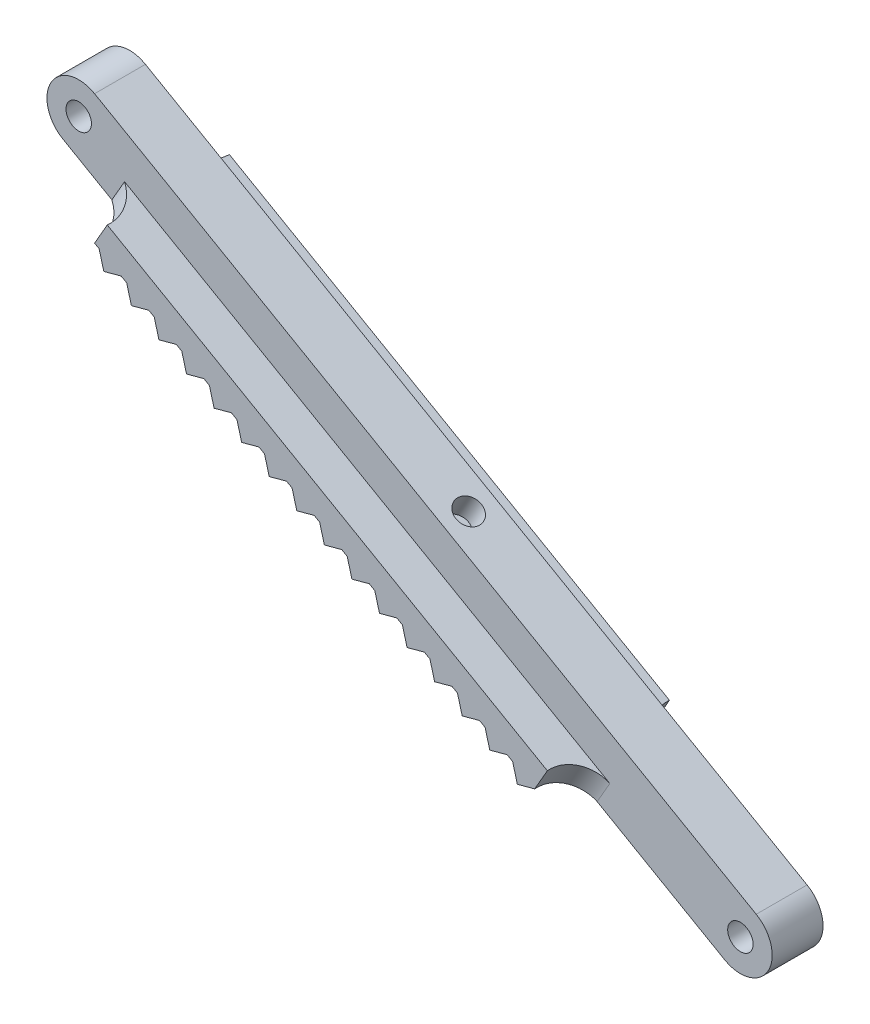
SolidWorks part; units mm, degrees
ref_plane "Спереди" through (0, 0, 0) normal (0, 0, 1) x (1, 0, 0)
ref_plane "Сверху" through (0, 0, 0) normal (0, 1, 0) x (1, 0, 0)
ref_plane "Справа" through (0, 0, 0) normal (1, 0, 0) x (0, 0, -1)
sketch "Sketch1" plane through (0, 0, 0) normal (0, 0, 1) x (1, 0, 0)
  line L0 (-5.265, 31.0446) -> (-57.3012, 60.9149) construction
  line L5 (-57.3012, 60.9149) -> (-5.265, 31.0446) construction
  line L6 (-56.0566, 63.083) -> (-4.0204, 33.2128)
  line L7 (-58.5458, 58.7467) -> (-6.5096, 28.8765)
  arc A2 (-56.0566, 63.083) -> (-58.5458, 58.7467) centre (-57.3012, 60.9149) ccw
  arc A3 (-6.5096, 28.8765) -> (-4.0204, 33.2128) centre (-5.265, 31.0446) ccw
  circle A4 centre (-57.3012, 60.9149) radius 1
  circle A5 centre (-5.265, 31.0446) radius 1
  point P2 (-31.2831, 45.9797)
  dimension "D3" = 2
  dimension "D1" = 60
  dimension "D2" = 5
extrude "Boss-Extrude1" add sketch "Sketch1" along normal blind 4
sketch "Sketch2" plane through (13.3435, 23.2454, 0) normal (0.4978, 0.8673, 0) x (0.8673, -0.4978, 0)
  line L0 (-50.3436, -2) -> (-46.6778, -2) construction
  line L2 (-48.4037, -4) -> (-48.4037, 0) construction
  circle A0 centre (-48.4037, -2) radius 1
  dimension "D1" = 2
extrude "Cut-Extrude1" cut sketch "Sketch2" against normal blind 2
sketch "Sketch3" plane through (0, 0, 0) normal (0, 0, -1) x (-1, 0, 0)
  line L0 (57.3012, 60.9149) -> (5.265, 31.0446) construction
sketch "Sketch4" plane through (10.8543, 18.9091, 0) normal (-0.4978, -0.8673, 0) x (0.8673, -0.4978, 0)
  line L0 (-77.201, 2) -> (-19.2917, 2) construction
  line L1 (-77.201, 4) -> (-77.201, 0) construction
  line L2 (-73.9186, 2) -> (-73.9186, 6.8) construction
  line L3 (-73.9186, 2) -> (-73.9186, -2.8) construction
  line L5 (-34.0104, 6.0447) -> (-34.0104, -2.4313) construction
  line L6 (-73.9186, 6.8) -> (-34.0104, 6.8)
  line L8 (-34.0104, -2.8) -> (-73.9186, -2.8)
  line L9 (-80.0213, 4) -> (-20.0213, 4) construction
  line L10 (-75.5799, 5.5) -> (-75.5799, 4) construction
  line L11 (-80.0213, 0) -> (-20.0213, 0) construction
  line L12 (-75.5799, 4) -> (-76.7485, 0)
  line L13 (-31.5748, 4) -> (-31.5748, 0)
  line L14 (-34.0104, -2.4313) -> (-34.0104, -2.8)
  arc A0 (-73.9186, 6.8) -> (-75.5799, 4) centre (-76.7401, 6.5812) cw
  arc A1 (-73.9186, -2.8) -> (-76.7485, 0) centre (-76.7188, -2.8) ccw
  arc A2 (-34.0104, 6.8) -> (-31.5748, 4) centre (-31.3926, 6.6178) ccw
  arc A3 (-31.5748, 0) -> (-34.0104, -2.8) centre (-31.3926, -2.6178) ccw
  dimension "D1" = 4.8
  dimension "D2" = 4.8
extrude "Boss-Extrude2" add sketch "Sketch4" against normal blind 2
sketch "Sketch5" plane through (0, 0, -2.8) normal (0, 0, -1) x (-1, 0, 0)
  line L0 (52.8991, 55.5053) -> (51.1646, 54.5096)
  line L1 (18.6419, 35.8407) -> (20.007, 35.4713)
  line L2 (20.007, 35.4713) -> (20.3765, 36.8364)
  line L3 (20.007, 35.4713) -> (19.5092, 36.3386) construction
  line L4 (20.8101, 37.0853) -> (22.1752, 36.7159)
  line L5 (22.1752, 36.7159) -> (22.5446, 38.081)
  line L6 (22.9783, 38.3299) -> (24.3434, 37.9605)
  line L7 (24.3434, 37.9605) -> (24.7128, 39.3256)
  line L8 (25.1464, 39.5745) -> (26.5115, 39.2051)
  line L9 (26.5115, 39.2051) -> (26.881, 40.5702)
  line L10 (27.3146, 40.8191) -> (28.6797, 40.4497)
  line L11 (28.6797, 40.4497) -> (29.0492, 41.8148)
  line L12 (29.4828, 42.0637) -> (30.8479, 41.6943)
  line L13 (30.8479, 41.6943) -> (31.2173, 43.0594)
  line L14 (31.651, 43.3083) -> (33.0161, 42.9389)
  line L15 (33.0161, 42.9389) -> (33.3855, 44.304)
  line L16 (33.8191, 44.5529) -> (35.1843, 44.1835)
  line L17 (35.1843, 44.1835) -> (35.5537, 45.5486)
  line L18 (35.9873, 45.7975) -> (37.3524, 45.4281)
  line L19 (37.3524, 45.4281) -> (37.7219, 46.7932)
  line L20 (38.1555, 47.0421) -> (39.5206, 46.6726)
  line L21 (39.5206, 46.6726) -> (39.89, 48.0378)
  line L22 (40.3237, 48.2867) -> (41.6888, 47.9172)
  line L23 (41.6888, 47.9172) -> (42.0582, 49.2823)
  line L24 (42.4919, 49.5313) -> (43.857, 49.1618)
  line L25 (43.857, 49.1618) -> (44.2264, 50.5269)
  line L26 (44.66, 50.7759) -> (46.0251, 50.4064)
  line L27 (46.0251, 50.4064) -> (46.3946, 51.7715)
  line L28 (46.8282, 52.0205) -> (48.1933, 51.651)
  line L29 (48.1933, 51.651) -> (48.5627, 53.0161)
  line L30 (48.9964, 53.265) -> (50.3615, 52.8956)
  line L31 (50.3615, 52.8956) -> (50.7309, 54.2607)
  line L32 (51.1646, 54.5096) -> (52.5297, 54.1402)
  line L33 (52.5297, 54.1402) -> (52.8991, 55.5053)
  line L34 (50.7309, 54.2607) -> (48.9964, 53.265)
  line L35 (48.5627, 53.0161) -> (46.8282, 52.0205)
  line L36 (46.3946, 51.7715) -> (44.66, 50.7759)
  line L37 (44.2264, 50.5269) -> (42.4919, 49.5313)
  line L38 (42.0582, 49.2823) -> (40.3237, 48.2867)
  line L39 (39.89, 48.0378) -> (38.1555, 47.0421)
  line L40 (37.7219, 46.7932) -> (35.9873, 45.7975)
  line L41 (35.5537, 45.5486) -> (33.8191, 44.5529)
  line L42 (33.3855, 44.304) -> (31.651, 43.3083)
  line L43 (31.2173, 43.0594) -> (29.4828, 42.0637)
  line L44 (20.3765, 36.8364) -> (18.6419, 35.8407)
  line L45 (22.5446, 38.081) -> (20.8101, 37.0853)
  line L46 (24.7128, 39.3256) -> (22.9783, 38.3299)
  line L47 (26.881, 40.5702) -> (25.1464, 39.5745)
  line L48 (29.0492, 41.8148) -> (27.3146, 40.8191)
  dimension "D1" = 1
  dimension "D2" = 16
extrude "Boss-Extrude3" add sketch "Sketch5" against normal up to surface (9.6 mm away) up to face at (-35.4497, 46.6419, 6.8)
